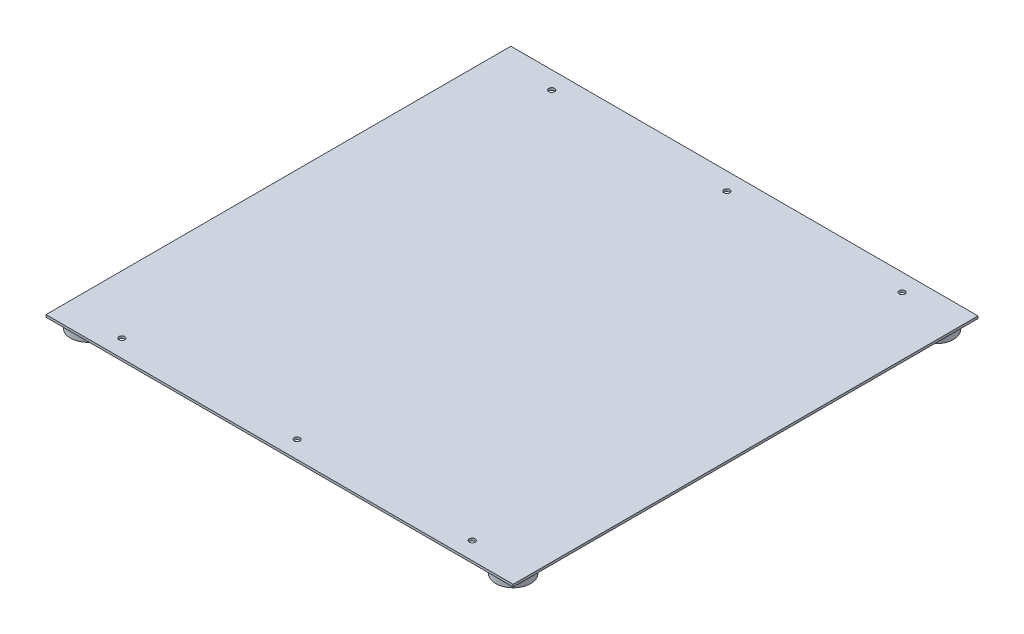
SolidWorks part; units mm, degrees
ref_plane "Front Plane" through (0, 0, 0) normal (0, 0, 1) x (1, 0, 0)
ref_plane "Top Plane" through (0, 0, 0) normal (0, 1, 0) x (1, 0, 0)
ref_plane "Right Plane" through (0, 0, 0) normal (1, 0, 0) x (0, 0, -1)
sketch "Sketch1" plane through (0, 0, 0) normal (0, 1, 0) x (1, 0, 0)
  line L0 (0, 30) -> (400, 30) construction
  line L1 (0, 0) -> (400, 0)
  line L2 (0, 0) -> (0, 398)
  line L3 (0, 398) -> (400, 398)
  line L4 (400, 0) -> (400, 398)
  line L5 (0, 15) -> (400, 15) construction
  line L6 (200, 15) -> (200, 0) construction
  line L7 (0, 199) -> (400, 199) construction
  circle A0 centre (50, 15) radius 2.5
  circle A1 centre (200, 15) radius 2.5
  circle A2 centre (350, 15) radius 2.5
  circle A3 centre (350, 383) radius 2.5
  circle A4 centre (200, 383) radius 2.5
  circle A5 centre (50, 383) radius 2.5
  dimension "D4" = 5
  dimension "D1" = 398
  dimension "D2" = 400
  dimension "D3" = 30
  dimension "D5" = 50
extrude "Boss-Extrude1" add sketch "Sketch1" along normal blind 2
sketch "Sketch2" plane through (0, 0, 0) normal (0, -1, 0) x (1, 0, 0)
  line L0 (0, 0) -> (400, 0) construction
  line L1 (0, -398) -> (0, 0) construction
  line L2 (200, 0) -> (200, -398) construction
  line L3 (400, -398) -> (0, -398) construction
  line L4 (0, -199) -> (400, -199) construction
  line L5 (400, 0) -> (400, -398) construction
  circle A0 centre (18, -18) radius 15
  circle A1 centre (382, -18) radius 15
  circle A2 centre (382, -380) radius 15
  circle A3 centre (18, -380) radius 15
  dimension "D1" = 30
  dimension "D2" = 18
  dimension "D3" = 18
extrude "Boss-Extrude2" add sketch "Sketch2" along normal blind 8
